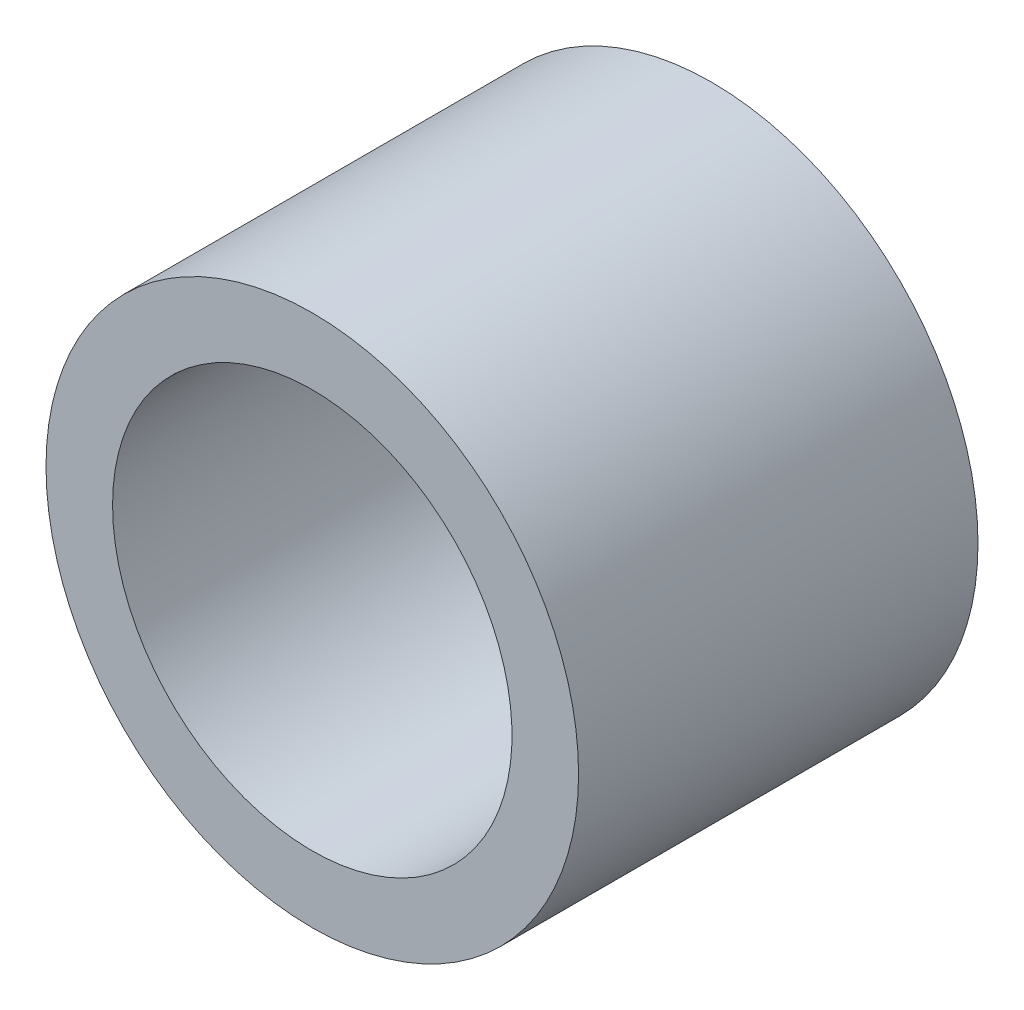
SolidWorks part; units mm, degrees
material "Commercial Bronze, UNS C22000 (90-10 Bronze)"
ref_plane "Front Plane" through (0, 0, 0) normal (0, 0, 1) x (1, 0, 0)
ref_plane "Top Plane" through (0, 0, 0) normal (0, 1, 0) x (1, 0, 0)
ref_plane "Right Plane" through (0, 0, 0) normal (1, 0, 0) x (0, 0, -1)
sketch "Sketch1" plane through (0, 0, 0) normal (0, 0, 1) x (1, 0, 0)
  circle A0 centre (0, 0) radius 9.525
  circle A1 centre (0, 0) radius 12.7
extrude "Boss-Extrude1" add sketch "Sketch1" along normal blind 19.05
